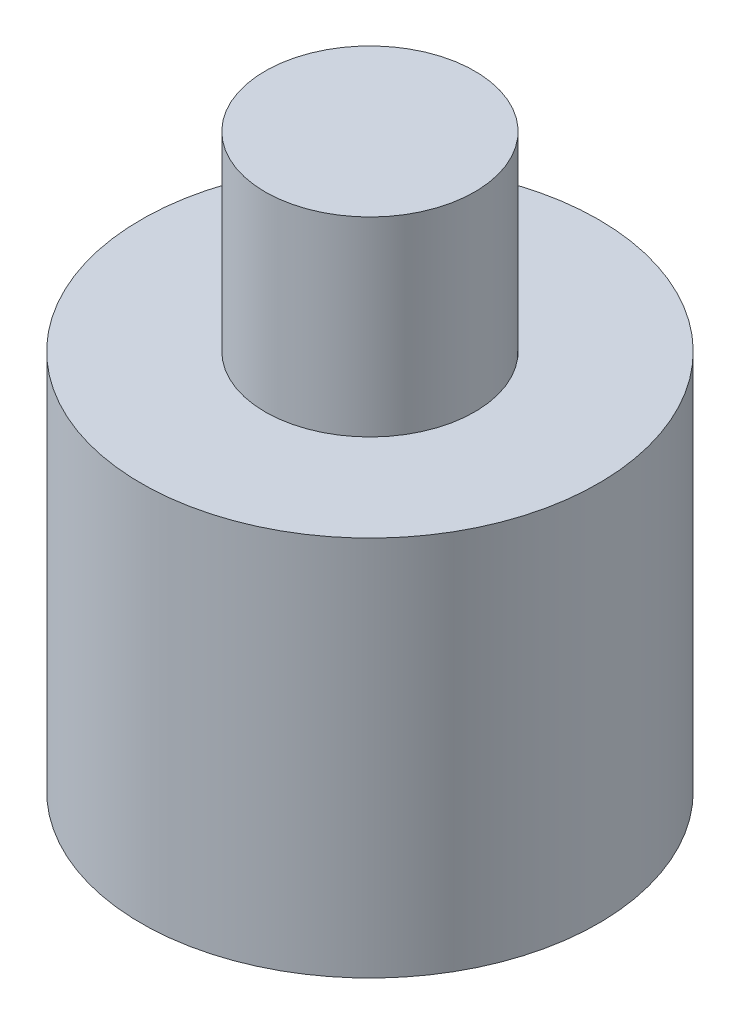
SolidWorks part; units mm, degrees
ref_plane "Front Plane" through (0, 0, 0) normal (0, 0, 1) x (1, 0, 0)
ref_plane "Top Plane" through (0, 0, 0) normal (0, 1, 0) x (1, 0, 0)
ref_plane "Right Plane" through (0, 0, 0) normal (1, 0, 0) x (0, 0, -1)
sketch "Sketch2" plane through (0, 0, 0) normal (0, 1, 0) x (1, 0, 0)
  circle A0 centre (0, 0) radius 2.75
  dimension "D1" = 5.5
extrude "Boss-Extrude1" add sketch "Sketch2" against normal blind 5
sketch "Sketch3" plane through (0, -5, 0) normal (0, -1, 0) x (-1, 0, 0)
  circle A0 centre (0, 0) radius 6
  dimension "D1" = 12
extrude "Boss-Extrude2" add sketch "Sketch3" along normal blind 10
